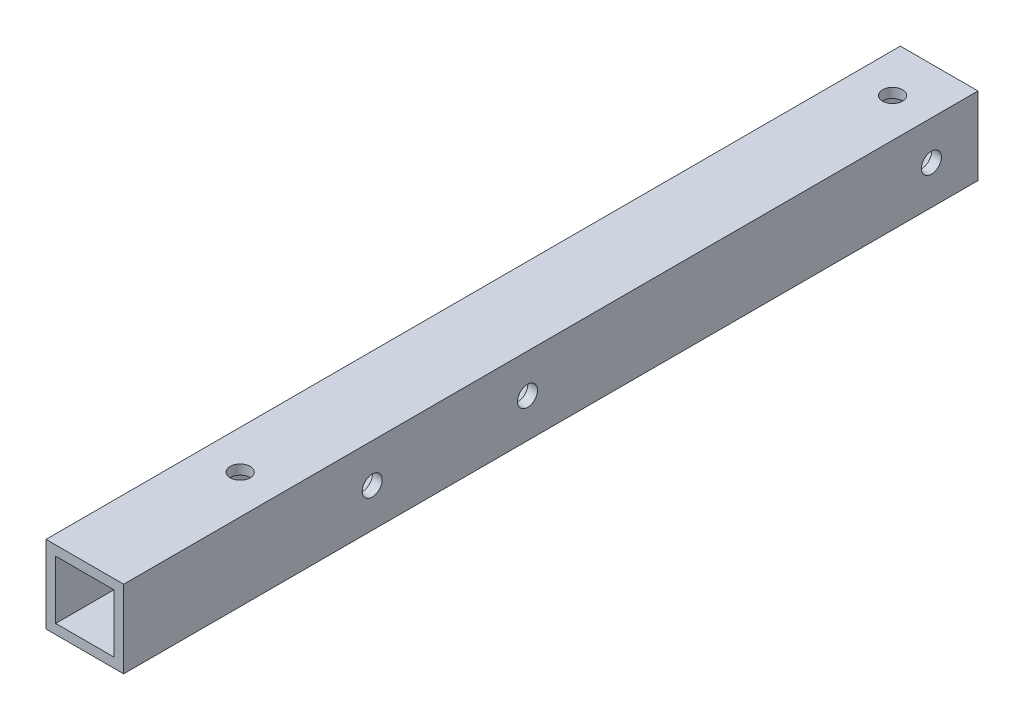
SolidWorks part; units mm, degrees
material "1060 Alloy"
ref_plane "Front Plane" through (0, 0, 0) normal (0, 0, 1) x (1, 0, 0)
ref_plane "Top Plane" through (0, 0, 0) normal (0, 1, 0) x (1, 0, 0)
ref_plane "Right Plane" through (0, 0, 0) normal (1, 0, 0) x (0, 0, -1)
sketch "Sketch2" plane through (0, 0, 0) normal (0, 0, 1) x (1, 0, 0)
  line L1 (12.7, -12.7) -> (-12.7, -12.7)
  line L2 (12.7, -12.7) -> (12.7, 12.7)
  line L3 (12.7, 12.7) -> (-12.7, 12.7)
  line L4 (-12.7, -12.7) -> (-12.7, 12.7)
  line L5 (12.7, -12.7) -> (-12.7, 12.7) construction
  line L6 (12.7, 12.7) -> (-12.7, -12.7) construction
  point P0 (0, 0)
  dimension "D1" = 25.4
extrude "Boss-Extrude1" add sketch "Sketch2" along normal blind 279.4 contours L4 L3 L2 L1
sketch "Sketch4" plane through (0, 0, 0) normal (0, 0, 1) x (1, 0, 0)
  line L0 (12.7, -12.7) -> (12.7, 12.7) construction
  line L1 (-9.525, -9.525) -> (9.525, -9.525)
  line L2 (-9.525, -9.525) -> (-9.525, 9.525)
  line L3 (-9.525, 9.525) -> (9.525, 9.525)
  line L4 (9.525, -9.525) -> (9.525, 9.525)
  line L5 (-9.525, -9.525) -> (9.525, 9.525) construction
  line L6 (-9.525, 9.525) -> (9.525, -9.525) construction
  line L7 (12.7, 12.7) -> (-12.7, 12.7) construction
  point P0 (0, 0)
  dimension "D1" = 3.175
  dimension "D2" = 3.175
extrude "Cut-Extrude1" cut sketch "Sketch4" along normal through all
sketch "Sketch5" plane through (0, 12.7, 0) normal (0, 1, 0) x (1, 0, 0)
  line L0 (12.7, 0) -> (-12.7, 0) construction
  circle A0 centre (0, -15.24) radius 3.2639
  point P5 (0, 0)
  dimension "D1" = 6.5278
  dimension "D2" = 15.24
extrude "Cut-Extrude2" cut sketch "Sketch5" against normal through all
sketch "Sketch6" plane through (0, 12.7, 0) normal (0, 1, 0) x (1, 0, 0)
  line L0 (12.7, -279.4) -> (-12.7, -279.4) construction
  line L1 (12.7, 0) -> (-12.7, 0) construction
  circle A0 centre (0, -228.6) radius 3.2639
  point P4 (0, -279.4)
  dimension "D1" = 6.5278
  dimension "D2" = 228.6
extrude "Cut-Extrude3" cut sketch "Sketch6" against normal through all
sketch "Sketch7" plane through (-12.7, 0, 0) normal (-1, 0, 0) x (0, 0, 1)
  line L0 (0, -12.7) -> (0, 12.7) construction
  circle A0 centre (15.24, 0) radius 3.2639
  point P4 (0, 0)
  dimension "D2" = 6.5278
  dimension "D1" = 15.24
extrude "Cut-Extrude4" cut sketch "Sketch7" against normal through all contours A0
sketch "Sketch8" plane through (-12.7, 0, 0) normal (-1, 0, 0) x (0, 0, 1)
  line L0 (0, -12.7) -> (0, 12.7) construction
  line L1 (279.4, -12.7) -> (279.4, 12.7) construction
  circle A0 centre (198.12, 0) radius 3.2639
  circle A1 centre (147.32, 0) radius 3.2639
  point P8 (279.4, 0)
  dimension "D1" = 6.5278
  dimension "D2" = 147.32
  dimension "D3" = 198.12
extrude "Cut-Extrude5" cut sketch "Sketch8" against normal through all
